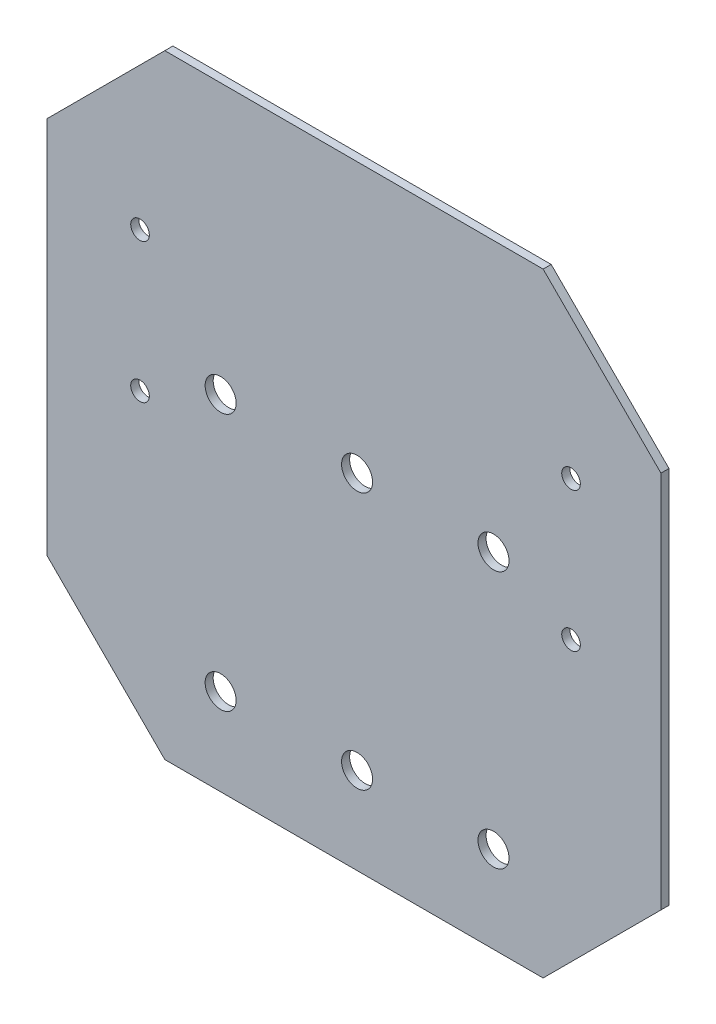
SolidWorks part; units mm, degrees
material "PVC Rigid"
ref_plane "Front Plane" through (0, 0, 0) normal (0, 0, 1) x (1, 0, 0)
ref_plane "Top Plane" through (0, 0, 0) normal (0, 1, 0) x (1, 0, 0)
ref_plane "Right Plane" through (0, 0, 0) normal (1, 0, 0) x (0, 0, -1)
sketch "Sketch1" plane through (0, 0, 0) normal (0, 0, 1) x (1, 0, 0)
  line L2 (-34.1753, 43.1861) -> (-34.1753, -17.8139)
  line L3 (-15.1753, 62.1861) -> (45.8247, 62.1861)
  line L4 (-15.1753, 62.1861) -> (-34.1753, 43.1861)
  line L11 (45.8247, 62.1861) -> (64.8247, 43.1861)
  line L12 (64.8247, 43.1861) -> (64.8247, -17.8139)
  line L13 (64.8247, -17.8139) -> (45.8247, -36.8139)
  line L14 (45.8247, -36.8139) -> (-15.1753, -36.8139)
  line L15 (-15.1753, -36.8139) -> (-34.1753, -17.8139)
  circle A0 centre (-6.1753, 18.6861) radius 2.5
  circle A1 centre (15.8247, 18.6861) radius 2.5
  circle A2 centre (37.8247, 18.6861) radius 2.5
  circle A3 centre (15.8247, -22.8139) radius 2.5
  circle A4 centre (37.8247, -22.8139) radius 2.5
  circle A5 centre (-6.1753, -22.8139) radius 2.5
  circle A6 centre (-19.1753, 12.6861) radius 1.5
  circle A7 centre (-19.1753, 35.1861) radius 1.5
  circle A8 centre (50.3247, 35.1861) radius 1.5
  circle A9 centre (50.3247, 12.6861) radius 1.5
extrude "Boss-Extrude1" add sketch "Sketch1" along normal blind 1.3
